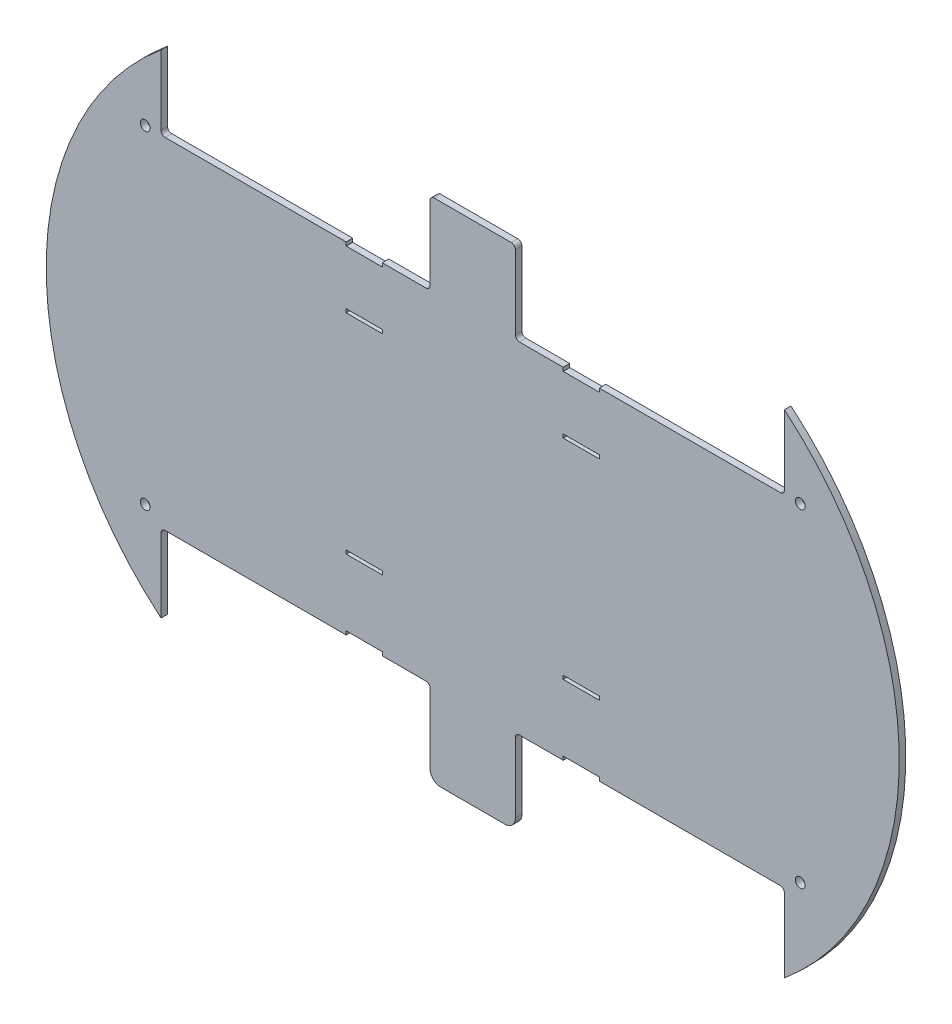
SolidWorks part; units mm, degrees
ref_plane "Front Plane" through (0, 0, 0) normal (0, 0, 1) x (1, 0, 0)
ref_plane "Top Plane" through (0, 0, 0) normal (0, 1, 0) x (1, 0, 0)
ref_plane "Right Plane" through (0, 0, 0) normal (1, 0, 0) x (0, 0, -1)
sketch "Szkic1" plane through (0, 0, 0) normal (0, 0, 1) x (1, 0, 0)
  line L0 (-139.7273, -79.5) -> (-120.189, -79.5)
  line L1 (-168.573, 50) -> (-168.573, 48.9)
  line L2 (0, 0) -> (-260, 0) construction
  line L3 (-223.75, 50) -> (-168.573, 50)
  line L4 (-143, 51.25) -> (-143, 73.75)
  line L5 (-225, 72.5) -> (-225, 51.25)
  line L6 (-141.75, 75) -> (-118.25, 75)
  line L7 (-223.75, -53.75) -> (-172.7811, -53.75)
  line L8 (-143, -55) -> (-143, -76.2376)
  line L10 (-130, 75) -> (-130, -75) construction
  line L12 (-225, -55) -> (-225, -77.5)
  line L16 (-157.573, 50) -> (-144.25, 50)
  line L20 (-157.573, -53.75) -> (-144.25, -53.75)
  line L29 (-117, 51.25) -> (-117, 73.75)
  line L38 (-102.427, -53.75) -> (-115.7693, -53.75)
  line L42 (-102.427, 50) -> (-115.75, 50)
  line L46 (-35, -55) -> (-35, -77.5)
  line L47 (-117, -54.9807) -> (-117, -76.25)
  line L48 (-36.25, -53.75) -> (-87.2189, -53.75)
  line L49 (-35, 72.5) -> (-35, 51.25)
  line L50 (-36.25, 50) -> (-91.427, 50)
  line L55 (-87.2189, -53.75) -> (-91.427, -53.75)
  line L72 (-168.573, 48.9) -> (-157.573, 48.9)
  line L73 (-157.573, 48.9) -> (-157.573, 50)
  line L74 (-157.573, -52.65) -> (-157.573, -53.75)
  line L77 (-172.7811, -53.75) -> (-168.573, -53.75)
  line L80 (-168.573, -53.75) -> (-168.573, -52.65)
  line L82 (-166.0903, -52.65) -> (-157.573, -52.65)
  line L85 (-102.427, -52.65) -> (-91.427, -52.65)
  line L87 (-102.427, -52.65) -> (-102.427, -53.75)
  line L89 (-91.427, 50) -> (-91.427, 48.9)
  line L90 (-91.427, 48.9) -> (-102.427, 48.9)
  line L91 (-102.427, 48.9) -> (-102.427, 50)
  line L92 (-91.427, -52.65) -> (-91.427, -53.75)
  line L93 (-168.573, -52.65) -> (-166.0903, -52.65)
  line L94 (-168.573, -32.4) -> (-168.573, -31.3)
  line L95 (-168.573, 32.4) -> (-157.573, 32.4)
  line L96 (-168.573, 32.4) -> (-168.573, 31.3)
  line L97 (-168.573, 31.3) -> (-157.573, 31.3)
  line L98 (-157.573, 32.4) -> (-157.573, 31.3)
  line L99 (-168.573, -31.3) -> (-157.573, -31.3)
  line L100 (-157.573, -32.4) -> (-157.573, -31.3)
  line L101 (-168.573, -32.4) -> (-157.573, -32.4)
  line L102 (-91.427, 31.3) -> (-102.427, 31.3)
  line L103 (-102.427, 32.4) -> (-102.427, 31.3)
  line L104 (-91.427, 32.4) -> (-102.427, 32.4)
  line L105 (-91.427, 32.4) -> (-91.427, 31.3)
  line L106 (-91.427, -32.4) -> (-102.427, -32.4)
  line L107 (-102.427, -32.4) -> (-102.427, -31.3)
  line L108 (-91.427, -31.3) -> (-102.427, -31.3)
  line L109 (-91.427, -31.3) -> (-91.427, -32.4)
  arc A0 (-225, -77.5) -> (-225, 72.5) centre (-162.1429, -2.5) cw
  circle A1 centre (-229.8183, 50.1102) radius 1.5
  circle A2 centre (-229.8183, -49.8898) radius 1.5
  circle A3 centre (-30.1817, -49.8898) radius 1.5
  circle A4 centre (-30.1817, 50.1102) radius 1.5
  arc A5 (-35, -77.5) -> (-35, 72.5) centre (-97.8571, -2.5) ccw
  arc A6 (-117, 51.25) -> (-115.75, 50) centre (-115.75, 51.25) ccw
  arc A7 (-36.25, 50) -> (-35, 51.25) centre (-36.25, 51.25) ccw
  arc A8 (-117, 73.75) -> (-118.25, 75) centre (-118.25, 73.75) ccw
  arc A9 (-141.75, 75) -> (-143, 73.75) centre (-141.75, 73.75) ccw
  arc A10 (-144.25, 50) -> (-143, 51.25) centre (-144.25, 51.25) ccw
  arc A11 (-143, -55) -> (-144.25, -53.75) centre (-144.25, -55) ccw
  arc A14 (-115.7693, -53.75) -> (-117, -54.9807) centre (-115.7693, -54.9807) ccw
  arc A15 (-35, -55) -> (-36.25, -53.75) centre (-36.25, -55) ccw
  arc A16 (-223.75, -53.75) -> (-225, -55) centre (-223.75, -55) ccw
  arc A17 (-225, 51.25) -> (-223.75, 50) centre (-223.75, 51.25) ccw
  arc A27 (-143, -76.2376) -> (-139.7273, -79.5) centre (-139.7376, -76.2376) ccw
  arc A28 (-120.189, -79.5) -> (-117, -76.25) centre (-120.189, -76.3104) ccw
  point P37 (-163.073, 48.9)
  point P59 (-91.427, -32.4)
  dimension "D12" = 1.1
  dimension "D19" = 97.8571
  dimension "D24" = 3
  dimension "D25" = 3
  dimension "D9" = 2.5
  dimension "D26" = 2.5
  dimension "D27" = 2.5
  dimension "D22" = 82
  dimension "D14" = 82
  dimension "D30" = 82
  dimension "D2" = 260
  dimension "D4" = 150
  dimension "D5" = 11
  dimension "D6" = 1.1
  dimension "D7" = 90
  dimension "D8" = 1.1
  dimension "D10" = 16.5
  dimension "D11" = 11
  dimension "D21" = 25
  dimension "D34" = 82
extrude "Dodanie-wyciągnięcie3" add sketch "Szkic1" along normal blind 2
